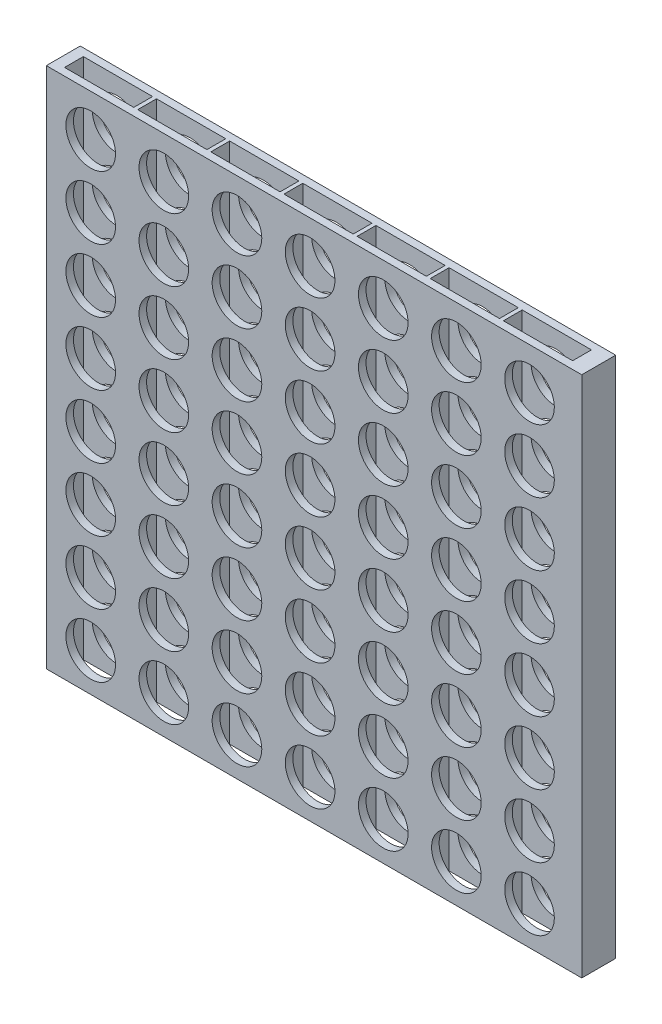
SolidWorks part; units mm, degrees
ref_plane "Front Plane" through (0, 0, 0) normal (0, 0, 1) x (1, 0, 0)
ref_plane "Top Plane" through (0, 0, 0) normal (0, 1, 0) x (1, 0, 0)
ref_plane "Right Plane" through (0, 0, 0) normal (1, 0, 0) x (0, 0, -1)
sketch "Sketch1" plane through (0, 0, 0) normal (0, 1, 0) x (1, 0, 0)
  line L1 (-130.175, 8.255) -> (130.175, 8.255)
  line L2 (-130.175, 8.255) -> (-130.175, -8.255)
  line L3 (-130.175, -8.255) -> (130.175, -8.255)
  line L4 (130.175, 8.255) -> (130.175, -8.255)
  line L5 (-130.175, 8.255) -> (130.175, -8.255) construction
  line L6 (-130.175, -8.255) -> (130.175, 8.255) construction
  point P0 (0, 0)
  dimension "D1" = 260.35
  dimension "D2" = 16.51
extrude "Boss-Extrude1" add sketch "Sketch1" along normal blind 254
sketch "Sketch2" plane through (0, 254, 0) normal (0, 1, 0) x (1, 0, 0)
  line L0 (-130.175, 8.255) -> (-130.175, -8.255) construction
  line L1 (-124.968, 4.572) -> (-91.313, 4.572)
  line L2 (-124.968, 4.572) -> (-124.968, -4.572)
  line L3 (-124.968, -4.572) -> (-91.313, -4.572)
  line L4 (-91.313, 4.572) -> (-91.313, -4.572)
  line L5 (-124.968, 4.572) -> (-124.968, 8.255) construction
  line L6 (130.175, 8.255) -> (-130.175, 8.255) construction
  line L7 (-124.968, -4.572) -> (-124.968, -8.255) construction
  line L8 (-130.175, -8.255) -> (130.175, -8.255) construction
  dimension "D1" = 5.207
  dimension "D2" = 9.144
  dimension "D3" = 33.655
extrude "Cut-Extrude1" cut sketch "Sketch2" against normal through all
pattern_linear "LPattern1" count 7 spacing 35.56 along (1, 0, 0) of "Cut-Extrude1"
sketch "Sketch3" plane through (0, 0, 8.255) normal (0, 0, 1) x (1, 0, 0)
  line L0 (-130.175, 254) -> (-130.175, 0) construction
  line L1 (-130.175, 254) -> (130.175, 254) construction
  circle A0 centre (-108.585, 233.68) radius 12.065
  dimension "D2" = 24.13
  dimension "D1" = 21.59
  dimension "D3" = 20.32
extrude "Cut-Extrude2" cut sketch "Sketch3" against normal through all
pattern_linear "LPattern2" count 7 spacing 35.56 along (1, 0, 0) count 8 spacing 30.734 along (0, -1, 0) of "Cut-Extrude2"
